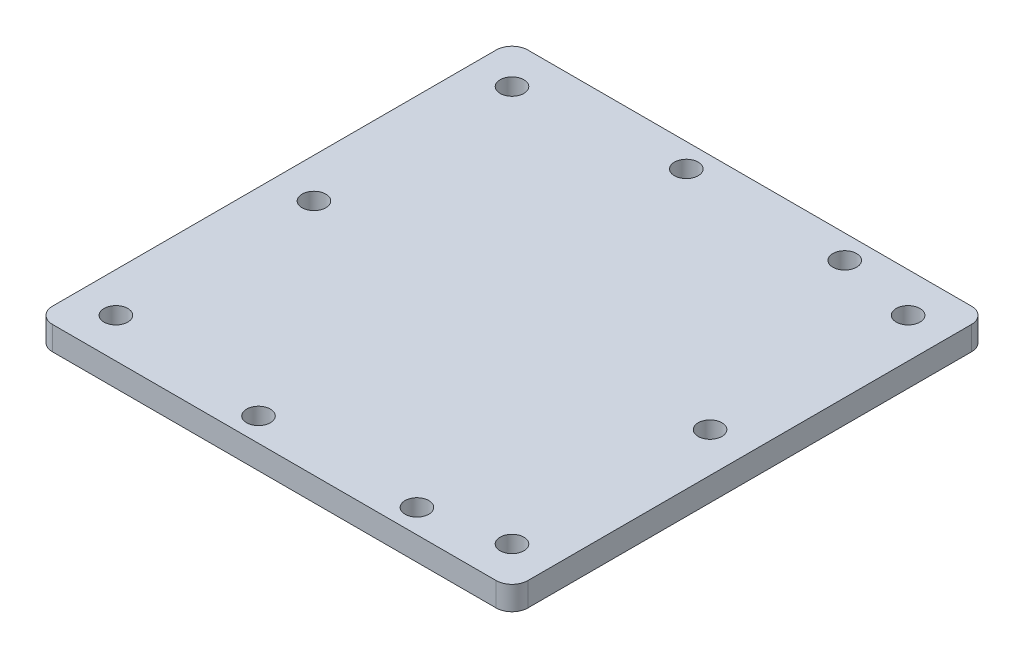
SolidWorks part; units mm, degrees
ref_plane "前视基准面" through (0, 0, 0) normal (0, 0, 1) x (1, 0, 0)
ref_plane "上视基准面" through (0, 0, 0) normal (0, 1, 0) x (1, 0, 0)
ref_plane "右视基准面" through (0, 0, 0) normal (1, 0, 0) x (0, 0, -1)
other "Configuration Table"
sketch "草图1" plane through (0, 0, 0) normal (0, 1, 0) x (1, 0, 0)
  line L0 (-5, 27) -> (15, 27) construction
  line L1 (-30, 30) -> (30, 30)
  line L2 (-30, 30) -> (-30, -30)
  line L3 (-30, -30) -> (30, -30)
  line L4 (30, 30) -> (30, -30)
  line L5 (-30, 30) -> (30, -30) construction
  line L6 (-30, -30) -> (30, 30) construction
  line L7 (0, 0) -> (30, 0) construction
  line L8 (0, 0) -> (0, -30) construction
  circle A0 centre (-5, 27) radius 1.5
  circle A1 centre (15, 27) radius 1.5
  circle A2 centre (15, -27) radius 1.5
  circle A3 centre (-5, -27) radius 1.5
  circle A4 centre (-25, 0) radius 1.5
  circle A5 centre (25, 0) radius 1.5
  point P0 (0, 0)
  dimension "D5" = 3
  dimension "D7" = 3
  dimension "D1" = 20
  dimension "D2" = 5
  dimension "D3" = 60
  dimension "D4" = 3
  dimension "D6" = 60
  dimension "D8" = 5
extrude "凸台-拉伸1" add sketch "草图1" along normal blind 3
sketch "草图2" plane through (0, 3, 0) normal (0, 1, 0) x (1, 0, 0)
  line L0 (30, 30) -> (-30, 30) construction
  line L1 (-25, -25) -> (25, -25) construction
  line L2 (-25, -25) -> (-25, 25) construction
  line L3 (-25, 25) -> (25, 25) construction
  line L4 (25, -25) -> (25, 25) construction
  line L5 (-25, -25) -> (25, 25) construction
  line L6 (-25, 25) -> (25, -25) construction
  line L7 (-30, 30) -> (-30, -30) construction
  circle A0 centre (-25, 25) radius 1.5
  circle A1 centre (25, 25) radius 1.5
  circle A2 centre (-25, -25) radius 1.5
  circle A3 centre (25, -25) radius 1.5
  point P0 (0, 0)
  dimension "D1" = 3
  dimension "D2" = 5
  dimension "D3" = 5
extrude "切除-拉伸1" cut sketch "草图2" against normal blind 10
fillet "圆角1" radius 2 4 edges at (30, 1.5, 30) (-30, 1.5, 30) (30, 1.5, -30) (-30, 1.5, -30)
